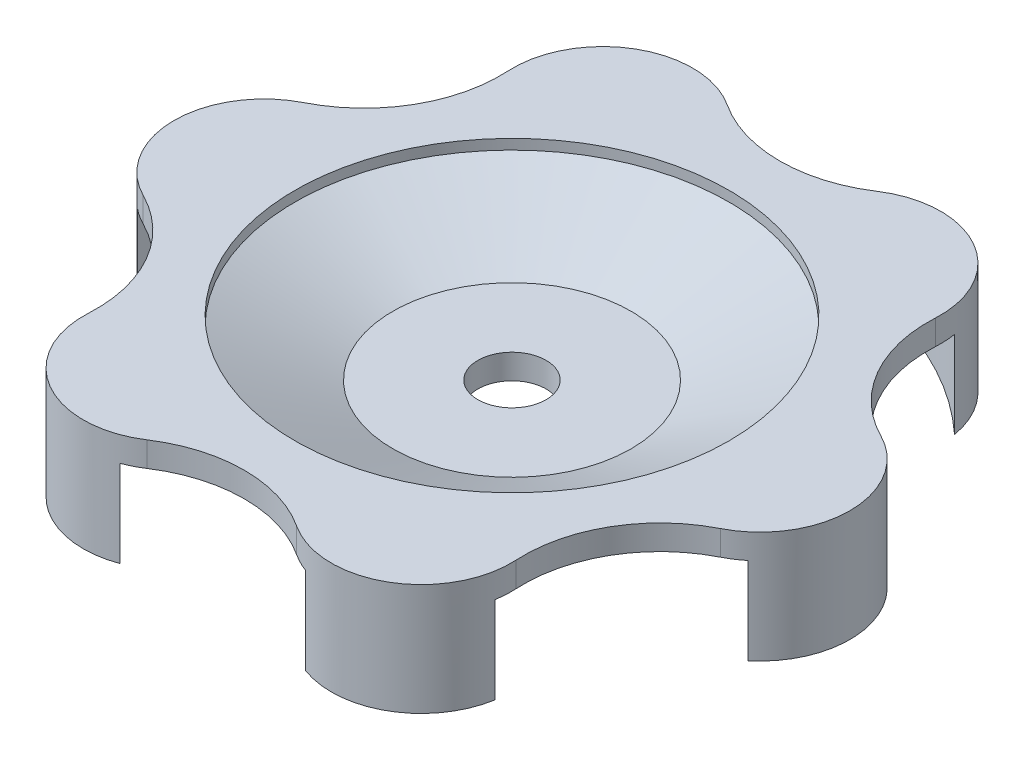
SolidWorks part; units mm, degrees
ref_plane "前视基准面" through (0, 0, 0) normal (0, 0, 1) x (1, 0, 0)
ref_plane "上视基准面" through (0, 0, 0) normal (0, 1, 0) x (1, 0, 0)
ref_plane "右视基准面" through (0, 0, 0) normal (1, 0, 0) x (0, 0, -1)
sketch "草图2" plane through (0, 0, 0) normal (0, 1, 0) x (1, 0, 0)
  circle A0 centre (0, 0) radius 2.75
  circle A1 centre (0, 0) radius 17.5
  dimension "D1" = 5.5
  dimension "D2" = 35
sketch "草图4" plane through (0, 0, 0) normal (0, 0, 1) x (1, 0, 0)
  line L0 (0, 0) -> (44.2939, 0) construction
  line L1 (17.5, 0) -> (-17.5, 0) construction
  line L2 (0, 0) -> (0, 29.9996) construction
  line L3 (2.75, 4.5) -> (9.6082, 4.5)
  line L4 (27.25, 9) -> (17.5, 9)
  line L5 (27.25, 9) -> (27.25, 0)
  line L6 (17.5, 9) -> (17.5, 8.18)
  line L7 (17.5, 8.18) -> (9.6082, 4.5)
  point P4 (2.75, 4.5)
  point P7 (27.25, 9)
  dimension "D1" = 4.5
  dimension "D2" = 54.5
  dimension "D3" = 9
  dimension "D4" = 0.82
  dimension "D5" = 25
  dimension "D6" = 35
  dimension "D7" = 5.5
revolve "旋转-薄壁1" add sketch "草图4" angle 360 about L2
sketch "草图7" plane through (0, 0, 0) normal (0, 1, 0) x (1, 0, 0)
  line L0 (-28.304, 0) -> (28.7187, 0) construction
  line L1 (0, 37.8063) -> (0, -30.3942) construction
  arc A0 (23.2659, -6.4727) -> (23.2659, 6.4727) centre (20, 0) ccw
  circle A2 centre (0, 0) radius 27.25 construction
  arc A3 (6.0274, -23.3852) -> (17.2385, -16.9125) centre (10, -17.3205) ccw
  arc A4 (-17.2385, -16.9125) -> (-6.0274, -23.3852) centre (-10, -17.3205) ccw
  arc A5 (-23.2659, 6.4727) -> (-23.2659, -6.4727) centre (-20, 0) ccw
  arc A6 (-6.0274, 23.3852) -> (-17.2385, 16.9125) centre (-10, 17.3205) ccw
  arc A7 (17.2385, 16.9125) -> (6.0274, 23.3852) centre (10, 17.3205) ccw
  arc A8 (23.2659, -6.4727) -> (17.2385, -16.9125) centre (28.2211, -16.2934) ccw
  arc A9 (6.0274, -23.3852) -> (-6.0274, -23.3852) centre (0, -32.5869) ccw
  arc A10 (-17.2385, -16.9125) -> (-23.2659, -6.4727) centre (-28.2211, -16.2934) ccw
  arc A11 (-23.2659, 6.4727) -> (-17.2385, 16.9125) centre (-28.2211, 16.2934) ccw
  arc A12 (-6.0274, 23.3852) -> (6.0274, 23.3852) centre (0, 32.5869) ccw
  arc A13 (17.2385, 16.9125) -> (23.2659, 6.4727) centre (28.2211, 16.2934) ccw
  arc A14 (-7.1233, 21.7122) -> (-15.2417, 17.0251) centre (-10, 17.3205) ccw
  arc A15 (-22.365, 4.6872) -> (-15.2417, 17.0251) centre (-28.2211, 16.2934) ccw
  arc A16 (-22.365, 4.6872) -> (-22.365, -4.6872) centre (-20, 0) ccw
  arc A17 (-15.2417, -17.0251) -> (-22.365, -4.6872) centre (-28.2211, -16.2934) ccw
  arc A18 (-15.2417, -17.0251) -> (-7.1233, -21.7122) centre (-10, -17.3205) ccw
  arc A19 (7.1233, -21.7122) -> (-7.1233, -21.7122) centre (0, -32.5869) ccw
  arc A20 (7.1233, -21.7122) -> (15.2417, -17.0251) centre (10, -17.3205) ccw
  arc A21 (22.365, -4.6872) -> (15.2417, -17.0251) centre (28.2211, -16.2934) ccw
  arc A22 (22.365, -4.6872) -> (22.365, 4.6872) centre (20, 0) ccw
  arc A23 (15.2417, 17.0251) -> (22.365, 4.6872) centre (28.2211, 16.2934) ccw
  arc A24 (15.2417, 17.0251) -> (7.1233, 21.7122) centre (10, 17.3205) ccw
  arc A25 (-7.1233, 21.7122) -> (7.1233, 21.7122) centre (0, 32.5869) ccw
  dimension "D1" = 6
  dimension "D2" = 6
  dimension "D3" = 2
extrude "切除-拉伸3" cut sketch "草图7" along normal blind 11 flip side to cut contours A4 A9 A3 A8 A0 A13 A7 A12 A6 A11 A5 A10
